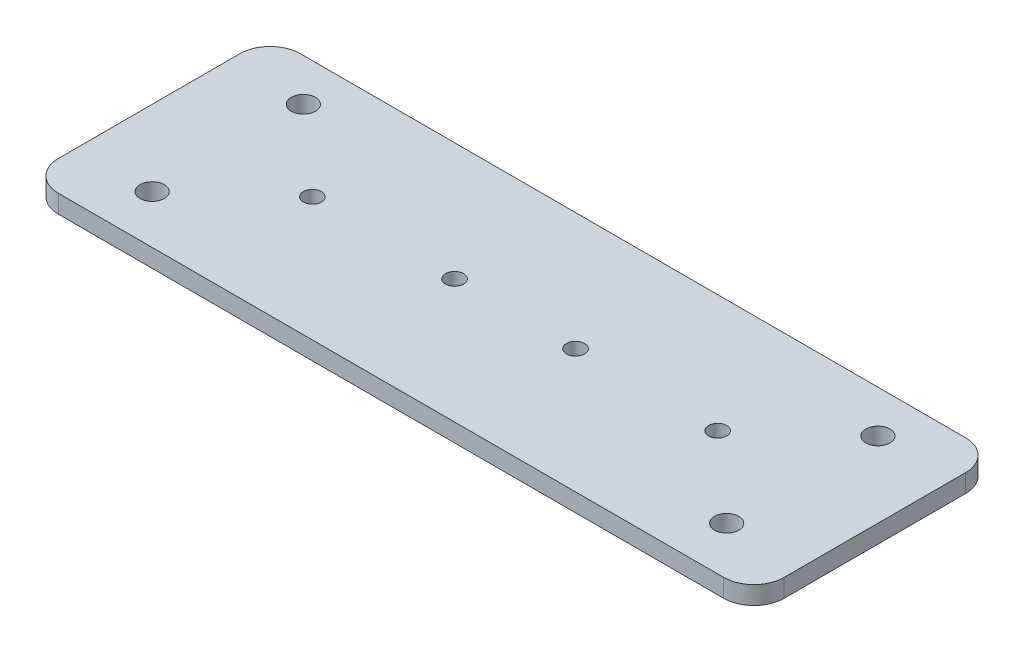
SolidWorks part; units mm, degrees
material "Thornel Mat VMA"
ref_plane "前视基准面" through (0, 0, 0) normal (0, 0, 1) x (1, 0, 0)
ref_plane "上视基准面" through (0, 0, 0) normal (0, 1, 0) x (1, 0, 0)
ref_plane "右视基准面" through (0, 0, 0) normal (1, 0, 0) x (0, 0, -1)
sketch "草图1" plane through (0, 0, 0) normal (0, 1, 0) x (1, 0, 0)
  line L0 (-60, 0) -> (60, 0)
  line L1 (0, 0) -> (0, 44.1583) construction
  line L2 (60, 0) -> (60, 40)
  line L3 (47.5, 33) -> (-47.5, 33) construction
  line L4 (47.5, 33) -> (47.5, 8) construction
  line L5 (47.5, 8) -> (-47.5, 8) construction
  line L6 (-47.5, 33) -> (-47.5, 8) construction
  line L7 (47.5, 33) -> (-47.5, 8) construction
  line L8 (47.5, 8) -> (-47.5, 33) construction
  line L9 (-25, 0) -> (-25, 62.7578) construction
  line L10 (25, 0) -> (25, 59.1873) construction
  line L11 (-33.5, 20.5) -> (33.5, 20.5) construction
  line L12 (-60, 0) -> (-60, 40)
  line L13 (-60, 40) -> (60, 40)
  circle A0 centre (10, 20.5) radius 1.5
  circle A1 centre (-10, 20.5) radius 1.5
  circle A2 centre (-33.5, 20.5) radius 1.5
  circle A3 centre (33.5, 20.5) radius 1.5
  circle A4 centre (-47.5, 8) radius 2
  circle A5 centre (-47.5, 33) radius 2
  circle A6 centre (47.5, 33) radius 2
  circle A7 centre (47.5, 8) radius 2
  point P5 (0, 0)
  point P6 (0, 20.5)
  point P18 (0, 20.5)
  dimension "D6" = 20
  dimension "D7" = 3
  dimension "D8" = 4
  dimension "D1" = 95
  dimension "D2" = 25
  dimension "D3" = 8
  dimension "D4" = 50
  dimension "D5" = 67
  dimension "D9" = 7
  dimension "D10" = 120
extrude "凸台-拉伸1" add sketch "草图1" along normal blind 3
fillet "圆角1" radius 5 4 edges at (-60, 1.5, 0) (-60, 1.5, -40) (60, 1.5, 0) (60, 1.5, -40)
